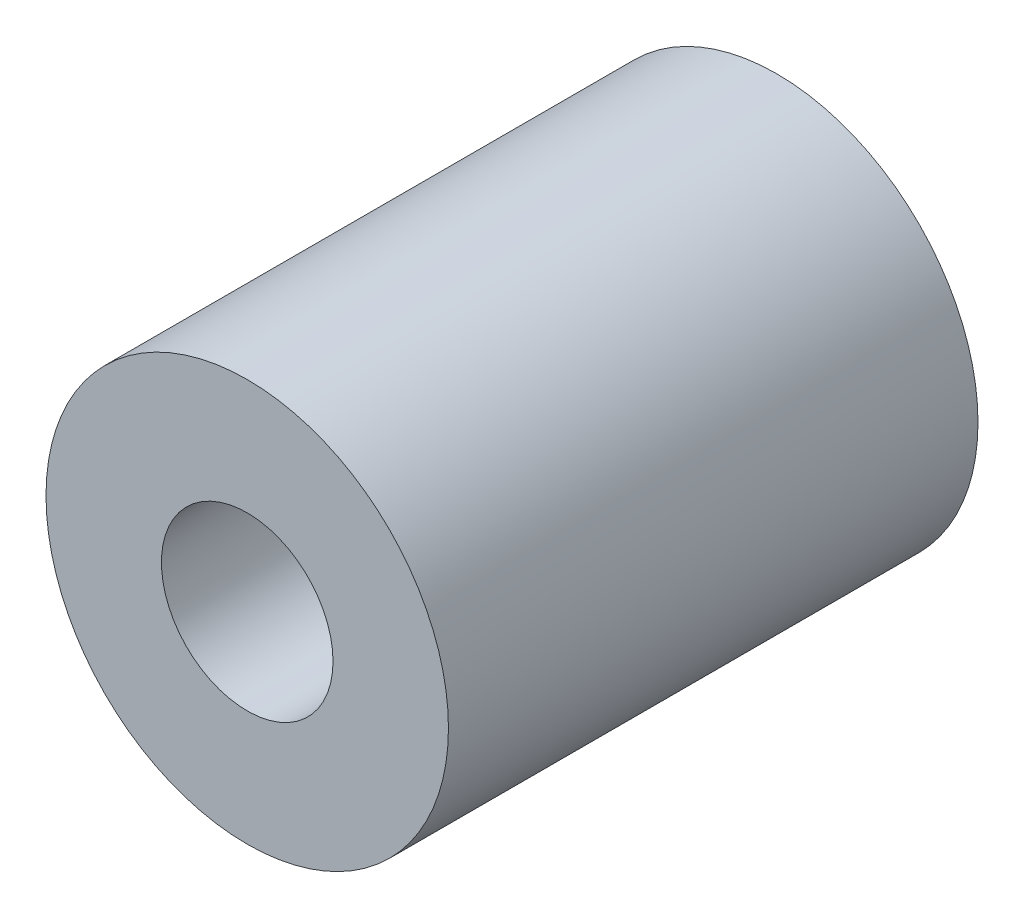
SolidWorks part; units mm, degrees
ref_plane "Alzado" through (0, 0, 0) normal (0, 0, 1) x (1, 0, 0)
ref_plane "Planta" through (0, 0, 0) normal (0, 1, 0) x (1, 0, 0)
ref_plane "Vista lateral" through (0, 0, 0) normal (1, 0, 0) x (0, 0, -1)
sketch "Croquis1" plane through (0, 0, 0) normal (0, 0, 1) x (1, 0, 0)
  circle A0 centre (0, 0) radius 9.5
  dimension "D1" = 19
extrude "Saliente-Extruir1" add sketch "Croquis1" along normal blind 25
sketch "Croquis2" plane through (0, 0, 25) normal (0, 0, 1) x (1, 0, 0)
  circle A0 centre (0, 0) radius 4.05
  dimension "D1" = 8.1
extrude "Cortar-Extruir1" cut sketch "Croquis2" against normal through all
